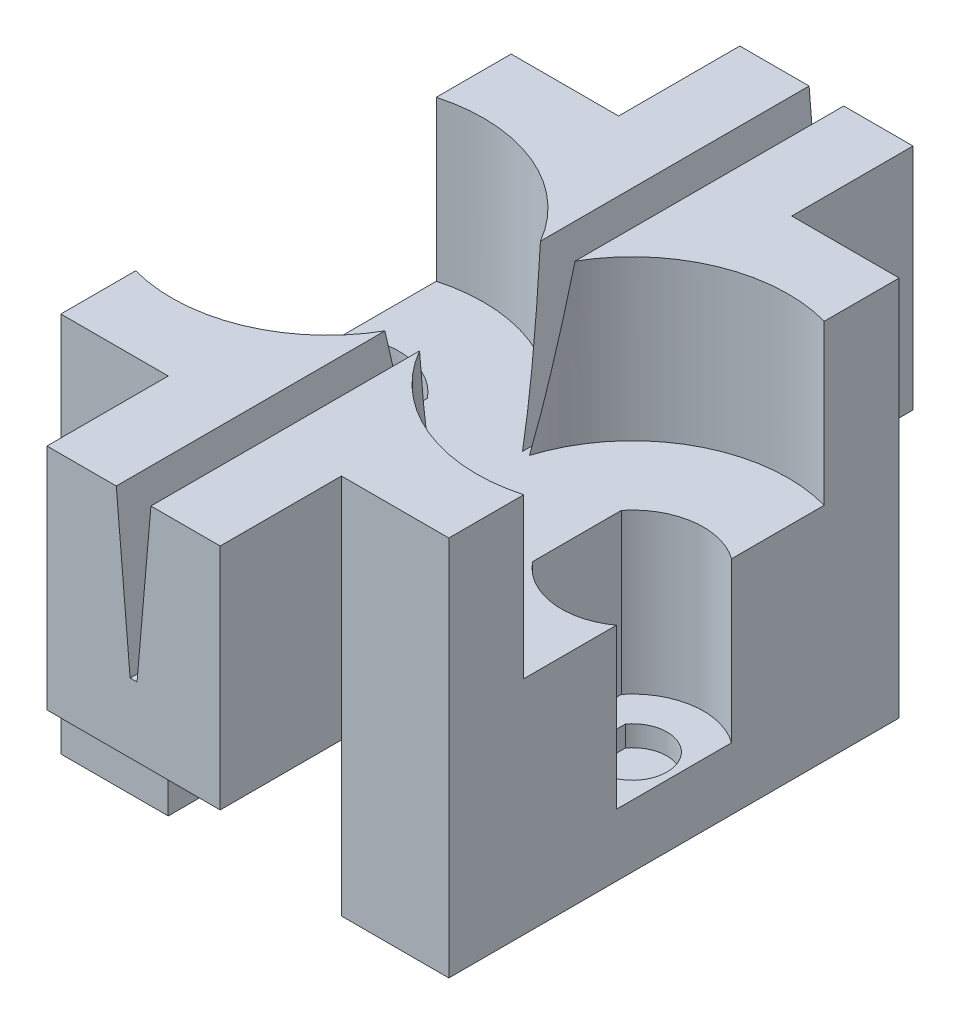
SolidWorks part; units mm, degrees
ref_plane "Front Plane" through (0, 0, 0) normal (0, 0, 1) x (1, 0, 0)
ref_plane "Top Plane" through (0, 0, 0) normal (0, 1, 0) x (1, 0, 0)
ref_plane "Right Plane" through (0, 0, 0) normal (1, 0, 0) x (0, 0, -1)
sketch "Sketch1" plane through (0, 0, 0) normal (0, 1, 0) x (1, 0, 0)
  line L1 (-28, -50) -> (28, -50)
  line L2 (-28, -50) -> (-28, 50)
  line L3 (-28, 50) -> (28, 50)
  line L4 (28, -50) -> (28, 50)
  line L5 (-28, -50) -> (28, 50) construction
  line L6 (-28, 50) -> (28, -50) construction
  point P0 (0, 0)
  dimension "D1" = 100
  dimension "D2" = 56
extrude "Boss-Extrude1" add sketch "Sketch1" along normal blind 55
sketch "Sketch3" plane through (0, 0, 50) normal (0, 0, 1) x (1, 0, 0)
  line L0 (0.5, 55) -> (0.5, 32) construction
  line L1 (-28, 55) -> (28, 55) construction
  line L3 (-28, 55) -> (-28, 0) construction
  line L4 (-0.5, 32) -> (-0.5, 55) construction
  line L5 (28, 55) -> (28, 0) construction
  line L11 (-0.5, 32) -> (-2.5, 55)
  line L13 (2.5, 55) -> (0.5, 32)
  line L14 (-0.5, 32) -> (0.5, 32)
  line L15 (-2.5, 55) -> (2.5, 55)
  dimension "D1" = 23
  dimension "D2" = 28.5
  dimension "D3" = 23
  dimension "D4" = 28.5
  dimension "D5" = 5
  dimension "D6" = 2
extrude "Cut-Extrude2" cut sketch "Sketch3" against normal through all
sketch "Sketch7" plane through (0, 55, 0) normal (0, 1, 0) x (1, 0, 0)
  line L0 (-0.5, 50) -> (-0.5, -50) construction
  line L3 (28, 50) -> (2.5, 50) construction
  circle A0 centre (22, 0) radius 10
  circle A1 centre (22, 0) radius 21.5 construction
  circle A2 centre (22, 0) radius 22.5
  dimension "D1" = 20
  dimension "D3" = 43
  dimension "D4" = 1
  dimension "D5" = 50
  dimension "D2" = 22.5
extrude "Cut-Extrude4" cut sketch "Sketch7" against normal blind 23
sketch "Sketch9" plane through (0, 55, 0) normal (0, 1, 0) x (1, 0, 0)
  line L0 (14, 6.408) -> (14, -6.408)
  circle A0 centre (22, 0) radius 10.25 construction
  arc A1 (14, 6.408) -> (14, -6.408) centre (22, 0) cw
  circle A2 centre (22, 0) radius 22.5 construction
  dimension "D1" = 20.5
  dimension "D2" = 8
extrude "Cut-Extrude5" cut sketch "Sketch9" against normal blind 46
sketch "Sketch10" plane through (0, 9, 0) normal (0, 1, 0) x (1, 0, 0)
  line L0 (18, 3) -> (18, -3)
  arc A1 (18, 3) -> (18, -3) centre (22, 0) cw
  arc A2 (28, 8.3104) -> (14, 6.408) centre (22, 0) ccw construction
  dimension "D1" = 6
  dimension "D2" = 5
  dimension "D3" = 0
  dimension "D4" = 0
extrude "Cut-Extrude6" cut sketch "Sketch10" against normal blind 3
sketch "Sketch11" plane through (0, 55, 0) normal (0, 1, 0) x (1, 0, 0)
  line L0 (14, 6.408) -> (14, -6.408)
  arc A0 (14, 6.408) -> (14, -6.408) centre (21.6771, 0) ccw
extrude "Cut-Extrude7" cut sketch "Sketch11" against normal blind 23
mirror "Mirror1" about plane through (0, 0, 0) normal (1, 0, 0) of "Cut-Extrude7", "Cut-Extrude4", "Cut-Extrude5", "Cut-Extrude6"
sketch "Sketch12" plane through (0, 55, 0) normal (0, 1, 0) x (1, 0, 0)
  line L0 (-2.5, 50) -> (-2.5, 11.225) construction
  line L1 (-28, 50) -> (-12.5, 50)
  line L2 (-28, 50) -> (-28, 32.5)
  line L3 (-28, 32.5) -> (-12.5, 32.5)
  line L4 (-12.5, 50) -> (-12.5, 32.5)
  line L5 (28, 50) -> (12.5, 50)
  line L6 (28, 50) -> (28, 32.5)
  line L7 (28, 32.5) -> (12.5, 32.5)
  line L8 (12.5, 50) -> (12.5, 32.5)
  line L9 (-28, -50) -> (-12.5, -50)
  line L10 (-28, -50) -> (-28, -32.5)
  line L11 (-28, -32.5) -> (-12.5, -32.5)
  line L12 (-12.5, -50) -> (-12.5, -32.5)
  line L13 (28, -50) -> (12.5, -50)
  line L14 (28, -50) -> (28, -32.5)
  line L15 (28, -32.5) -> (12.5, -32.5)
  line L16 (12.5, -50) -> (12.5, -32.5)
  line L17 (2.5, 50) -> (2.5, 11.225) construction
  line L18 (2.5, -11.225) -> (2.5, -50) construction
  line L19 (-2.5, -11.225) -> (-2.5, -50) construction
  arc A1 (-28, -21.6852) -> (-2.5, -11.225) centre (-22, 0) ccw construction
  arc A2 (0.5, -6.6332) -> (28, -21.6852) centre (22, 0) ccw construction
  arc A3 (28, 21.6852) -> (2.5, 11.225) centre (22, 0) ccw construction
  arc A4 (-2.5, 11.225) -> (-28, 21.6852) centre (-22, 0) ccw construction
  dimension "D5" = 32.5
  dimension "D1" = 10
  dimension "D2" = 10
  dimension "D3" = 10
  dimension "D4" = 10
  dimension "D6" = 32.5
  dimension "D7" = 32.5
  dimension "D8" = 32.5
extrude "Cut-Extrude8" cut sketch "Sketch12" against normal through all
sketch "Sketch13" plane through (0, 0, 50) normal (0, 0, 1) x (1, 0, 0)
  line L0 (12.5, 0) -> (12.5, 55) construction
  line L1 (-12.5, 0) -> (12.5, 0)
  line L2 (-12.5, 0) -> (-12.5, 22)
  line L3 (-12.5, 22) -> (12.5, 22)
  line L4 (12.5, 0) -> (12.5, 22)
  dimension "D1" = 22
extrude "Cut-Extrude9" cut sketch "Sketch13" against normal through all
